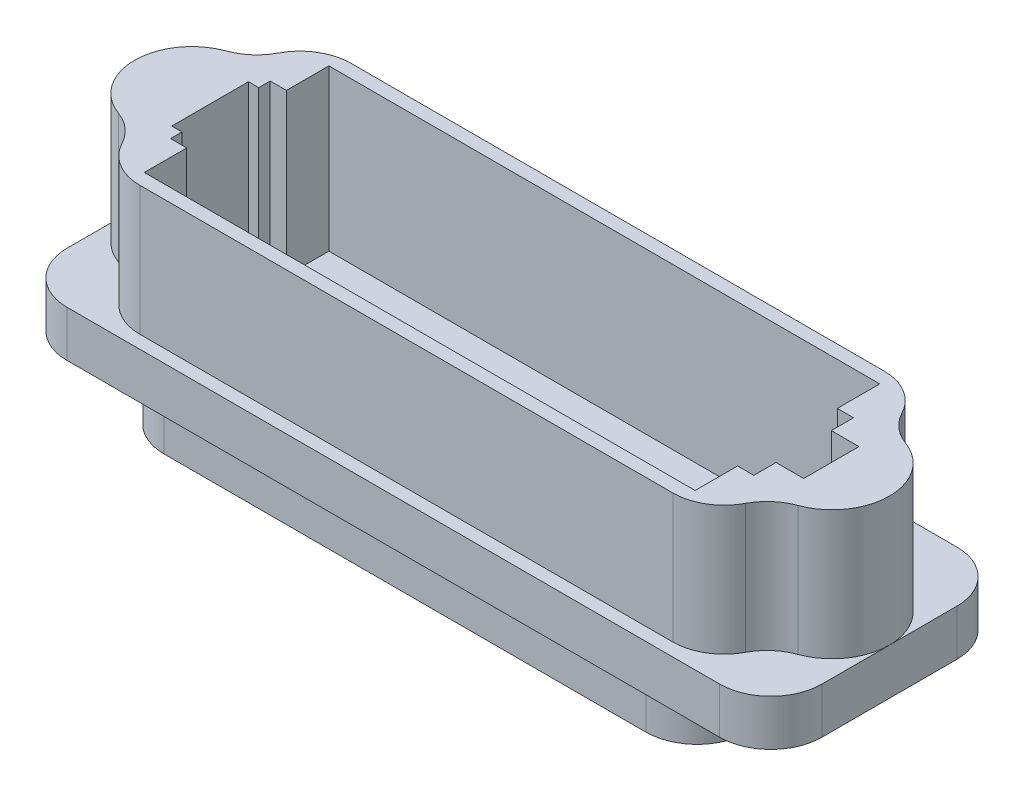
SolidWorks part; units mm, degrees
ref_plane "Спереди" through (0, 0, 0) normal (0, 0, 1) x (1, 0, 0)
ref_plane "Сверху" through (0, 0, 0) normal (0, 1, 0) x (1, 0, 0)
ref_plane "Справа" through (0, 0, 0) normal (1, 0, 0) x (0, 0, -1)
other "Configuration Table"
sketch "Эскиз1" plane through (0, 0, 0) normal (0, 1, 0) x (1, 0, 0)
  line L1 (-31.885, 11.595) -> (31.885, 11.595)
  line L2 (-36.885, 6.595) -> (-36.885, -6.595)
  line L3 (-31.885, -11.595) -> (31.885, -11.595)
  line L4 (36.885, 6.595) -> (36.885, -6.595)
  line L5 (-36.885, 11.595) -> (36.885, -11.595) construction
  line L6 (-36.885, -11.595) -> (36.885, 11.595) construction
  arc A0 (-31.885, 11.595) -> (-36.885, 6.595) centre (-31.885, 6.595) ccw
  arc A1 (-31.885, -11.595) -> (-36.885, -6.595) centre (-31.885, -6.595) cw
  arc A2 (36.885, -6.595) -> (31.885, -11.595) centre (31.885, -6.595) cw
  arc A3 (36.885, 6.595) -> (31.885, 11.595) centre (31.885, 6.595) ccw
  point P0 (0, 0)
  dimension "D1" = 5
  dimension "D2" = 73.77
  dimension "D3" = 23.19
extrude "Бобышка-Вытянуть1" add sketch "Эскиз1" along normal mid plane 4.5 contours A3 L4 A2 L3 A1 L2 A0 L1
sketch "Эскиз2" plane through (0, 2.25, 0) normal (0, 1, 0) x (1, 0, 0)
  line L0 (-31.285, 0) -> (31.285, 0) construction
  line L1 (-26.04, 10.32) -> (26.04, 10.32)
  line L2 (-31.04, 5.32) -> (-31.04, -5.32)
  line L3 (-26.04, -10.32) -> (26.04, -10.32)
  line L4 (31.04, 5.32) -> (31.04, -5.32)
  line L5 (-31.04, 10.32) -> (31.04, -10.32) construction
  line L6 (-31.04, -10.32) -> (31.04, 10.32) construction
  line L7 (-31.285, 5.6) -> (31.285, 5.6)
  line L8 (-31.285, -5.6) -> (31.285, -5.6)
  line L9 (36.885, 6.595) -> (36.885, -6.595) construction
  arc A0 (-31.285, 5.6) -> (-31.285, -5.6) centre (-31.285, 0) ccw
  arc A1 (31.285, -5.6) -> (31.285, 5.6) centre (31.285, 0) ccw
  arc A2 (-26.04, -10.32) -> (-31.04, -5.32) centre (-26.04, -5.32) cw
  arc A3 (26.04, -10.32) -> (31.04, -5.32) centre (26.04, -5.32) ccw
  arc A4 (31.04, 5.32) -> (26.04, 10.32) centre (26.04, 5.32) ccw
  arc A5 (-26.04, 10.32) -> (-31.04, 5.32) centre (-26.04, 5.32) ccw
  point P0 (0, 0)
  point P8 (0, 0)
  dimension "D1" = 5.6
  dimension "D4" = 5
  dimension "D2" = 20.64
  dimension "D3" = 62.08
extrude "Бобышка-Вытянуть2" add sketch "Эскиз2" along normal blind 12.61 contours A5 L7 A0 L8 A2 L2 | L3 A3 L8 A2 | L7 A5 L2 A2 L8 A3 L4 A4 | L1 A5 L7 A4 | A4 L4 A3 L8 A1 L7
fillet "Скругление1" radius 5 4 edges at (-31.0322, 8.555, 5.6) (-31.0322, 8.555, -5.6) (31.0322, 8.555, -5.6) (31.0322, 8.555, 5.6)
sketch "Эскиз3" plane through (0, -2.25, 0) normal (0, -1, 0) x (1, 0, 0)
  line L1 (-23.555, 10.465) -> (23.555, 10.465)
  line L2 (-28.555, 5.465) -> (-28.555, -5.465)
  line L3 (-23.555, -10.465) -> (23.555, -10.465)
  line L4 (28.555, 5.465) -> (28.555, -5.465)
  line L5 (-28.555, 10.465) -> (28.555, -10.465) construction
  line L6 (-28.555, -10.465) -> (28.555, 10.465) construction
  arc A0 (23.555, 10.465) -> (28.555, 5.465) centre (23.555, 5.465) cw
  arc A1 (28.555, -5.465) -> (23.555, -10.465) centre (23.555, -5.465) cw
  arc A2 (-23.555, -10.465) -> (-28.555, -5.465) centre (-23.555, -5.465) cw
  arc A3 (-28.555, 5.465) -> (-23.555, 10.465) centre (-23.555, 5.465) cw
  point P0 (0, 0)
  dimension "D1" = 5
  dimension "D2" = 20.93
  dimension "D3" = 57.11
extrude "Бобышка-Вытянуть3" add sketch "Эскиз3" along normal blind 4.3
sketch "Эскиз4" plane through (0, 14.86, 0) normal (0, 1, 0) x (1, 0, 0)
  line L0 (-26.04, 10.32) -> (26.04, 10.32) construction
  line L1 (-26.915, 9.02) -> (26.915, 9.02)
  line L2 (-26.915, 9.02) -> (-26.915, -9.02)
  line L3 (-26.915, -9.02) -> (26.915, -9.02)
  line L4 (26.915, 9.02) -> (26.915, -9.02)
  line L5 (-26.915, 9.02) -> (26.915, -9.02) construction
  line L6 (-26.915, -9.02) -> (26.915, 9.02) construction
  line L7 (0, 0) -> (0, -19.6637) construction
  line L8 (-28.5, 4.87) -> (28.5, 4.87)
  line L9 (-28.5, 4.87) -> (-28.5, -4.87)
  line L10 (-28.5, -4.87) -> (28.5, -4.87)
  line L11 (28.5, 4.87) -> (28.5, -4.87)
  line L12 (-28.5, 4.87) -> (28.5, -4.87) construction
  line L13 (-28.5, -4.87) -> (28.5, 4.87) construction
  line L14 (25.795, -2.7) -> (31.205, -2.7)
  line L15 (25.795, -2.7) -> (25.795, 2.7)
  line L16 (25.795, 2.7) -> (31.205, 2.7)
  line L17 (31.205, -2.7) -> (31.205, 2.7)
  line L18 (25.795, -2.7) -> (31.205, 2.7) construction
  line L19 (25.795, 2.7) -> (31.205, -2.7) construction
  line L21 (-27.5, 3.75) -> (-29.5, 3.75)
  line L22 (-27.5, 3.75) -> (-27.5, -3.75)
  line L23 (-27.5, -3.75) -> (-29.5, -3.75)
  line L24 (-29.5, 3.75) -> (-29.5, -3.75)
  line L25 (-27.5, 3.75) -> (-29.5, -3.75) construction
  line L26 (-27.5, -3.75) -> (-29.5, 3.75) construction
  point P0 (0, 0)
  point P8 (0, 0)
  point P13 (28.5, 0)
  point P20 (-28.5, 0)
  dimension "D1" = 1.3
  dimension "D2" = 53.83
  dimension "D3" = 57
  dimension "D4" = 9.74
  dimension "D5" = 62.41
  dimension "D6" = 5.4
  dimension "D7" = 7.5
  dimension "D8" = 2
extrude "Вырез-Вытянуть1" cut sketch "Эскиз4" against normal blind 15.68 and the other way through all contours L15 L16 L4 L8 L2 L10 L14 | L2 L8 L4 L1 | L21 L24 L23 L9 | L23 L22 L21 L9 | L22 L23 L9 L10 L2 L8 L21 | L10 L2 L3 L4 | L16 L4 L14 L11 | L14 L17 L16 L11 | L16 L15 L14 L4 | L14 L4 L10 L11 | L4 L16 L11 L8
